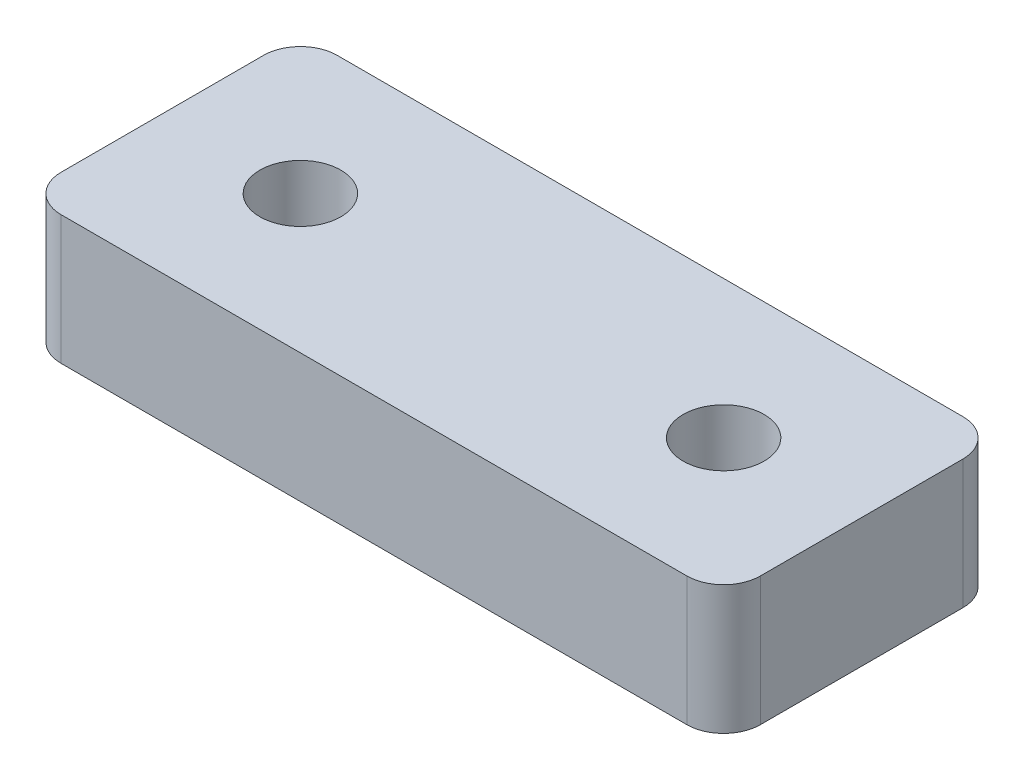
SolidWorks part; units mm, degrees
material "ABS"
ref_plane "前视基准面" through (0, 0, 0) normal (0, 0, 1) x (1, 0, 0)
ref_plane "上视基准面" through (0, 0, 0) normal (0, 1, 0) x (1, 0, 0)
ref_plane "右视基准面" through (0, 0, 0) normal (1, 0, 0) x (0, 0, -1)
sketch "草图1" plane through (0, 0, 0) normal (0, 1, 0) x (1, 0, 0)
  line L0 (-19, 0) -> (19, 0) construction
  line L1 (-19, 7.5) -> (19, 7.5)
  line L2 (-19, 7.5) -> (-19, -7.5)
  line L3 (-19, -7.5) -> (19, -7.5)
  line L4 (19, 7.5) -> (19, -7.5)
  line L5 (0, -3.3) -> (0, 3.3) construction
  circle A0 centre (-11.5, 0) radius 2.2
  circle A2 centre (11.5, 0) radius 2.2
  dimension "D3" = 23
  dimension "D4" = 4.4
  dimension "D1" = 38
  dimension "D2" = 15
extrude "凸台-拉伸1" add sketch "草图1" along normal blind 7
fillet "圆角1" radius 2 4 edges at (-19, 3.5, 7.5) (-19, 3.5, -7.5) (19, 3.5, -7.5) (19, 3.5, 7.5)
